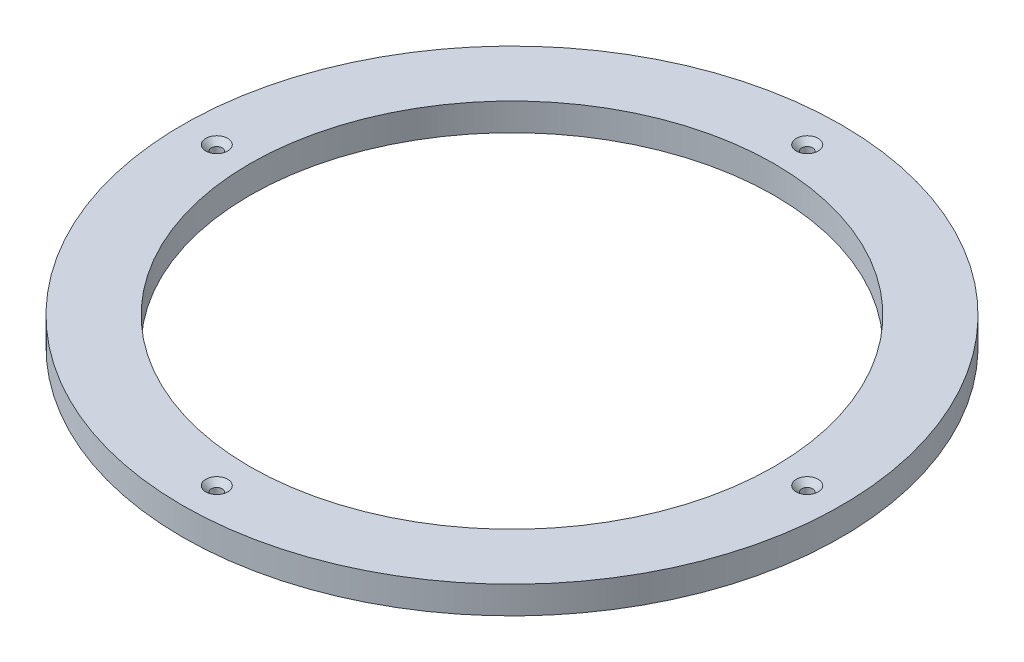
SolidWorks part; units mm, degrees
ref_plane "Front Plane" through (0, 0, 0) normal (0, 0, 1) x (1, 0, 0)
ref_plane "Top Plane" through (0, 0, 0) normal (0, 1, 0) x (1, 0, 0)
ref_plane "Right Plane" through (0, 0, 0) normal (1, 0, 0) x (0, 0, -1)
sketch "Sketch1" plane through (0, 0, 0) normal (0, 1, 0) x (1, 0, 0)
  circle A0 centre (0, 0) radius 60
  dimension "D1" = 120
extrude "Boss-Extrude1" add sketch "Sketch1" along normal blind 5
sketch "Sketch2" plane through (0, 5, 0) normal (0, 1, 0) x (1, 0, 0)
  line L0 (0, 0) -> (0, 60) construction
  circle A0 centre (0, 0) radius 60 construction
  circle A1 centre (0, 53.75) radius 1
  point P8 (0, 0)
  point P9 (0, 0)
  dimension "D2" = 2
  dimension "D1" = 53.75
extrude "Cut-Extrude1" cut sketch "Sketch2" against normal up to surface (5 mm away) up to face at (0, 0, 60)
chamfer "Chamfer1" distance 1 angle 45 1 edges at (0, 5, -52.75)
pattern_circular "CirPattern1" count 4 over 360 about axis through (0, 0, 0) along (0, 1, 0) of "Chamfer1", "Cut-Extrude1"
sketch "Sketch3" plane through (0, 5, 0) normal (0, 1, 0) x (1, 0, 0)
  circle A0 centre (0, 0) radius 47.75
  dimension "D1" = 95.5
extrude "Cut-Extrude2" cut sketch "Sketch3" against normal up to surface (5 mm away) up to face at (-53.75, 0, 1)
